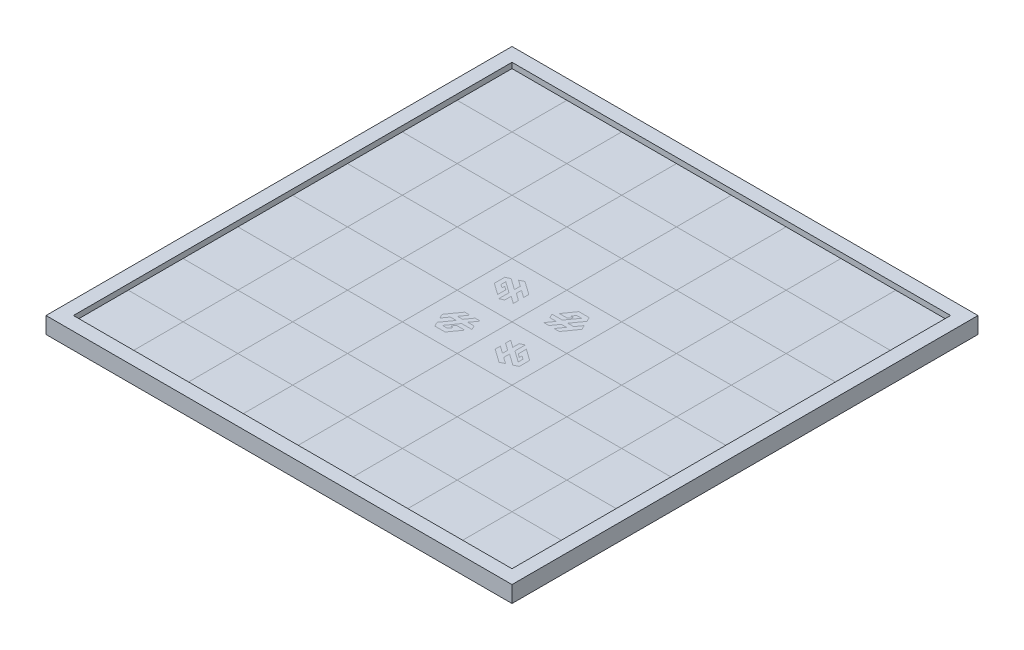
SolidWorks part; units mm, degrees
ref_plane "Front Plane" through (0, 0, 0) normal (0, 0, 1) x (1, 0, 0)
ref_plane "Top Plane" through (0, 0, 0) normal (0, 1, 0) x (1, 0, 0)
ref_plane "Right Plane" through (0, 0, 0) normal (1, 0, 0) x (0, 0, -1)
sketch "Sketch1" plane through (0, 0, 0) normal (0, 1, 0) x (1, 0, 0)
  line L1 (0, 0) -> (177.8, 0) construction
  line L2 (0, 0) -> (0, 177.8) construction
  line L3 (0, 177.8) -> (177.8, 177.8) construction
  line L4 (177.8, 0) -> (177.8, 177.8) construction
  line L5 (-12.7, 190.5) -> (190.5, 190.5)
  line L6 (-12.7, 190.5) -> (-12.7, -12.7)
  line L7 (-12.7, -12.7) -> (190.5, -12.7)
  line L8 (190.5, 190.5) -> (190.5, -12.7)
  circle A0 centre (0, 0) radius 9.652 construction
  circle A1 centre (0, 25.4) radius 9.652 construction
  circle A2 centre (0, 50.8) radius 9.652 construction
  circle A3 centre (0, 76.2) radius 9.652 construction
  circle A4 centre (0, 101.6) radius 9.652 construction
  circle A5 centre (0, 127) radius 9.652 construction
  circle A6 centre (0, 152.4) radius 9.652 construction
  circle A7 centre (0, 177.8) radius 9.652 construction
  circle A8 centre (25.4, 25.4) radius 9.652 construction
  circle A9 centre (25.4, 50.8) radius 9.652 construction
  circle A10 centre (25.4, 76.2) radius 9.652 construction
  circle A11 centre (25.4, 101.6) radius 9.652 construction
  circle A12 centre (25.4, 127) radius 9.652 construction
  circle A13 centre (25.4, 152.4) radius 9.652 construction
  circle A14 centre (25.4, 177.8) radius 9.652 construction
  circle A15 centre (50.8, 25.4) radius 9.652 construction
  circle A16 centre (50.8, 50.8) radius 9.652 construction
  circle A17 centre (50.8, 76.2) radius 9.652 construction
  circle A18 centre (50.8, 101.6) radius 9.652 construction
  circle A19 centre (50.8, 127) radius 9.652 construction
  circle A20 centre (50.8, 152.4) radius 9.652 construction
  circle A21 centre (50.8, 177.8) radius 9.652 construction
  circle A22 centre (76.2, 25.4) radius 9.652 construction
  circle A23 centre (76.2, 50.8) radius 9.652 construction
  circle A24 centre (76.2, 76.2) radius 9.652 construction
  circle A25 centre (76.2, 101.6) radius 9.652 construction
  circle A26 centre (76.2, 127) radius 9.652 construction
  circle A27 centre (76.2, 152.4) radius 9.652 construction
  circle A28 centre (76.2, 177.8) radius 9.652 construction
  circle A29 centre (101.6, 25.4) radius 9.652 construction
  circle A30 centre (101.6, 50.8) radius 9.652 construction
  circle A31 centre (101.6, 76.2) radius 9.652 construction
  circle A32 centre (101.6, 101.6) radius 9.652 construction
  circle A33 centre (101.6, 127) radius 9.652 construction
  circle A34 centre (101.6, 152.4) radius 9.652 construction
  circle A35 centre (101.6, 177.8) radius 9.652 construction
  circle A36 centre (127, 25.4) radius 9.652 construction
  circle A37 centre (127, 50.8) radius 9.652 construction
  circle A38 centre (127, 76.2) radius 9.652 construction
  circle A39 centre (127, 101.6) radius 9.652 construction
  circle A40 centre (127, 127) radius 9.652 construction
  circle A41 centre (127, 152.4) radius 9.652 construction
  circle A42 centre (127, 177.8) radius 9.652 construction
  circle A43 centre (152.4, 25.4) radius 9.652 construction
  circle A44 centre (152.4, 50.8) radius 9.652 construction
  circle A45 centre (152.4, 76.2) radius 9.652 construction
  circle A46 centre (152.4, 101.6) radius 9.652 construction
  circle A47 centre (152.4, 127) radius 9.652 construction
  circle A48 centre (152.4, 152.4) radius 9.652 construction
  circle A49 centre (152.4, 177.8) radius 9.652 construction
  circle A50 centre (177.8, 25.4) radius 9.652 construction
  circle A51 centre (177.8, 50.8) radius 9.652 construction
  circle A52 centre (177.8, 76.2) radius 9.652 construction
  circle A53 centre (177.8, 101.6) radius 9.652 construction
  circle A54 centre (177.8, 127) radius 9.652 construction
  circle A55 centre (177.8, 152.4) radius 9.652 construction
  circle A56 centre (177.8, 177.8) radius 9.652 construction
  circle A57 centre (25.4, 0) radius 9.652 construction
  circle A58 centre (50.8, 0) radius 9.652 construction
  circle A59 centre (76.2, 0) radius 9.652 construction
  circle A60 centre (101.6, 0) radius 9.652 construction
  circle A61 centre (127, 0) radius 9.652 construction
  circle A62 centre (152.4, 0) radius 9.652 construction
  circle A63 centre (177.8, 0) radius 9.652 construction
  dimension "D1" = 19.304
  dimension "D7" = 3.048
  dimension "D8" = 3.048
  dimension "D9" = 3.048
  dimension "D10" = 3.048
  dimension "D4" = 25.4
  dimension "D5" = 25.4
  dimension "D2" = 8
  dimension "D3" = 8
extrude "Boss-Extrude1" add sketch "Sketch1" along normal blind 5.08
sketch "Sketch2" plane through (0, 0, 0) normal (0, -1, 0) x (1, 0, 0)
  line L8 (-19.05, 19.05) -> (-19.05, -196.85)
  line L9 (-19.05, -196.85) -> (196.85, -196.85)
  line L10 (196.85, -196.85) -> (196.85, 19.05)
  line L11 (196.85, 19.05) -> (-19.05, 19.05)
  line L12 (-19.05, 19.05) -> (-19.05, -196.85)
  line L13 (-19.05, -196.85) -> (196.85, -196.85)
  line L14 (196.85, -196.85) -> (196.85, 19.05)
  line L15 (196.85, 19.05) -> (-19.05, 19.05)
  line L16 (-12.7, 12.7) -> (-12.7, -190.5)
  line L17 (-12.7, -190.5) -> (190.5, -190.5)
  line L18 (190.5, -190.5) -> (190.5, 12.7)
  line L19 (190.5, 12.7) -> (-12.7, 12.7)
  line L20 (-12.7, 12.7) -> (-12.7, -190.5)
  line L21 (-12.7, -190.5) -> (190.5, -190.5)
  line L22 (190.5, -190.5) -> (190.5, 12.7)
  line L23 (190.5, 12.7) -> (-12.7, 12.7)
  dimension "D1" = 6.35
  dimension "D2" = 0
extrude "Boss-Extrude2" add sketch "Sketch2" against normal blind 7.62
sketch "Sketch4" plane through (0, 7.62, 0) normal (0, 1, 0) x (1, 0, 0)
  line L0 (190.5, 190.5) -> (-12.7, 190.5) construction
  line L1 (190.5, 190.5) -> (-12.7, 190.5)
  line L2 (-12.7, -12.7) -> (-12.7, 190.5) construction
  line L3 (-12.7, -12.7) -> (-12.7, 190.5)
  line L4 (190.5, 165.1) -> (-12.7, 165.1)
  line L5 (190.5, 139.7) -> (-12.7, 139.7)
  line L6 (190.5, 114.3) -> (-12.7, 114.3)
  line L7 (190.5, 88.9) -> (-12.7, 88.9)
  line L8 (190.5, 63.5) -> (-12.7, 63.5)
  line L9 (190.5, 38.1) -> (-12.7, 38.1)
  line L10 (190.5, 12.7) -> (-12.7, 12.7)
  line L11 (12.7, -12.7) -> (12.7, 190.5)
  line L12 (38.1, -12.7) -> (38.1, 190.5)
  line L13 (63.5, -12.7) -> (63.5, 190.5)
  line L14 (88.9, -12.7) -> (88.9, 190.5)
  line L15 (114.3, -12.7) -> (114.3, 190.5)
  line L16 (139.7, -12.7) -> (139.7, 190.5)
  line L17 (165.1, -12.7) -> (165.1, 190.5)
  dimension "D2" = 25.4
  dimension "D3" = 8
  dimension "D4" = 25.4
  dimension "D1" = 8
split line "Split Line1"
ref_plane "Mirror Plane 1" through (0, 0, -88.9) normal (0, 0, 1) x (1, 0, 0)
ref_plane "Plane2" through (88.9, 0, 0) normal (1, 0, 0) x (0, 0, -1)
sketch "Sketch5" plane through (0, 5.08, 0) normal (0, 1, 0) x (1, 0, 0)
  line L0 (104.1362, 206.4027) -> (277.4695, 206.4027) construction
  line L1 (74.0494, 81.8343) -> (69.6938, 75.7121)
  line L2 (69.6938, 75.7121) -> (70.6525, 73.6706)
  line L3 (70.6525, 73.6706) -> (72.694, 76.5401)
  line L4 (72.694, 76.5401) -> (75.4281, 76.5401)
  line L5 (75.4281, 76.5401) -> (71.7397, 71.3558)
  line L6 (71.7397, 71.3558) -> (72.694, 69.3238)
  line L7 (72.694, 69.3238) -> (77.5045, 69.3238)
  line L8 (77.5045, 69.3238) -> (81.2609, 74.6037)
  line L9 (81.2609, 74.6037) -> (77.4793, 74.6037)
  line L10 (77.4793, 74.6037) -> (76.3014, 72.9479)
  line L11 (76.3014, 72.9479) -> (77.5891, 72.9479)
  line L12 (77.5891, 72.9479) -> (76.4564, 71.3558)
  line L13 (76.4564, 71.3558) -> (74.2335, 71.3558)
  line L14 (74.2335, 71.3558) -> (77.9219, 76.5401)
  line L15 (77.9219, 76.5401) -> (82.7029, 76.5401)
  line L16 (82.7029, 76.5401) -> (81.7977, 78.4675)
  line L17 (81.7977, 78.4675) -> (78.8318, 78.4675)
  line L18 (78.8318, 78.4675) -> (81.2272, 81.8343)
  line L19 (81.2272, 81.8343) -> (78.8517, 81.8343)
  line L20 (78.8517, 81.8343) -> (76.4564, 78.4675)
  line L21 (76.4564, 78.4675) -> (74.061, 78.4675)
  line L22 (74.061, 78.4675) -> (76.4564, 81.8343)
  line L23 (76.4564, 81.8343) -> (74.0494, 81.8343)
  line L24 (81.8343, 103.7506) -> (75.7121, 108.1062)
  line L25 (75.7121, 108.1062) -> (73.6706, 107.1475)
  line L26 (73.6706, 107.1475) -> (76.5401, 105.106)
  line L27 (76.5401, 105.106) -> (76.5401, 102.3719)
  line L28 (76.5401, 102.3719) -> (71.3558, 106.0603)
  line L29 (71.3558, 106.0603) -> (69.3238, 105.106)
  line L30 (69.3238, 105.106) -> (69.3238, 100.2955)
  line L31 (69.3238, 100.2955) -> (74.6037, 96.5391)
  line L32 (74.6037, 96.5391) -> (74.6037, 100.3207)
  line L33 (74.6037, 100.3207) -> (72.9479, 101.4986)
  line L34 (72.9479, 101.4986) -> (72.9479, 100.2109)
  line L35 (72.9479, 100.2109) -> (71.3558, 101.3436)
  line L36 (71.3558, 101.3436) -> (71.3558, 103.5665)
  line L37 (71.3558, 103.5665) -> (76.5401, 99.8781)
  line L38 (76.5401, 99.8781) -> (76.5401, 95.0971)
  line L39 (76.5401, 95.0971) -> (78.4675, 96.0023)
  line L40 (78.4675, 96.0023) -> (78.4675, 98.9682)
  line L41 (78.4675, 98.9682) -> (81.8343, 96.5728)
  line L42 (81.8343, 96.5728) -> (81.8343, 98.9483)
  line L43 (81.8343, 98.9483) -> (78.4675, 101.3436)
  line L44 (78.4675, 101.3436) -> (78.4675, 103.739)
  line L45 (78.4675, 103.739) -> (81.8343, 101.3436)
  line L46 (81.8343, 101.3436) -> (81.8343, 103.7506)
  line L47 (103.7506, 95.9657) -> (108.1062, 102.0879)
  line L48 (108.1062, 102.0879) -> (107.1475, 104.1294)
  line L49 (107.1475, 104.1294) -> (105.106, 101.2599)
  line L50 (105.106, 101.2599) -> (102.3719, 101.2599)
  line L51 (102.3719, 101.2599) -> (106.0603, 106.4442)
  line L52 (106.0603, 106.4442) -> (105.106, 108.4762)
  line L53 (105.106, 108.4762) -> (100.2955, 108.4762)
  line L54 (100.2955, 108.4762) -> (96.5391, 103.1963)
  line L55 (96.5391, 103.1963) -> (100.3207, 103.1963)
  line L56 (100.3207, 103.1963) -> (101.4986, 104.8521)
  line L57 (101.4986, 104.8521) -> (100.2109, 104.8521)
  line L58 (100.2109, 104.8521) -> (101.3436, 106.4442)
  line L59 (101.3436, 106.4442) -> (103.5665, 106.4442)
  line L60 (103.5665, 106.4442) -> (99.8781, 101.2599)
  line L61 (99.8781, 101.2599) -> (95.0971, 101.2599)
  line L62 (95.0971, 101.2599) -> (96.0023, 99.3325)
  line L63 (96.0023, 99.3325) -> (98.9682, 99.3325)
  line L64 (98.9682, 99.3325) -> (96.5728, 95.9657)
  line L65 (96.5728, 95.9657) -> (98.9483, 95.9657)
  line L66 (98.9483, 95.9657) -> (101.3436, 99.3325)
  line L67 (101.3436, 99.3325) -> (103.739, 99.3325)
  line L68 (103.739, 99.3325) -> (101.3436, 95.9657)
  line L69 (101.3436, 95.9657) -> (103.7506, 95.9657)
  line L70 (95.9657, 74.0494) -> (102.0879, 69.6938)
  line L71 (102.0879, 69.6938) -> (104.1294, 70.6525)
  line L72 (104.1294, 70.6525) -> (101.2599, 72.694)
  line L73 (101.2599, 72.694) -> (101.2599, 75.4281)
  line L74 (101.2599, 75.4281) -> (106.4442, 71.7397)
  line L75 (106.4442, 71.7397) -> (108.4762, 72.694)
  line L76 (108.4762, 72.694) -> (108.4762, 77.5045)
  line L77 (108.4762, 77.5045) -> (103.1963, 81.2609)
  line L78 (103.1963, 81.2609) -> (103.1963, 77.4793)
  line L79 (103.1963, 77.4793) -> (104.8521, 76.3014)
  line L80 (104.8521, 76.3014) -> (104.8521, 77.5891)
  line L81 (104.8521, 77.5891) -> (106.4442, 76.4564)
  line L82 (106.4442, 76.4564) -> (106.4442, 74.2335)
  line L83 (106.4442, 74.2335) -> (101.2599, 77.9219)
  line L84 (101.2599, 77.9219) -> (101.2599, 82.7029)
  line L85 (101.2599, 82.7029) -> (99.3325, 81.7977)
  line L86 (99.3325, 81.7977) -> (99.3325, 78.8318)
  line L87 (99.3325, 78.8318) -> (95.9657, 81.2272)
  line L88 (95.9657, 81.2272) -> (95.9657, 78.8517)
  line L89 (95.9657, 78.8517) -> (99.3325, 76.4564)
  line L90 (99.3325, 76.4564) -> (99.3325, 74.061)
  line L91 (99.3325, 74.061) -> (95.9657, 76.4564)
  line L92 (95.9657, 76.4564) -> (95.9657, 74.0494)
  point P23 (88.9, 88.9)
  point P99 (88.9, 88.9)
  dimension "D1" = 1.9613
  dimension "D2" = 1.9356
  dimension "D3" = 1.9273
  dimension "D4" = 2.032
  dimension "D5" = 2.032
  dimension "D6" = 7.5136
  dimension "D7" = 2.032
  dimension "D8" = 0.762
  dimension "D9" = 2.032
  dimension "D10" = 4
split line "Split Line2"
